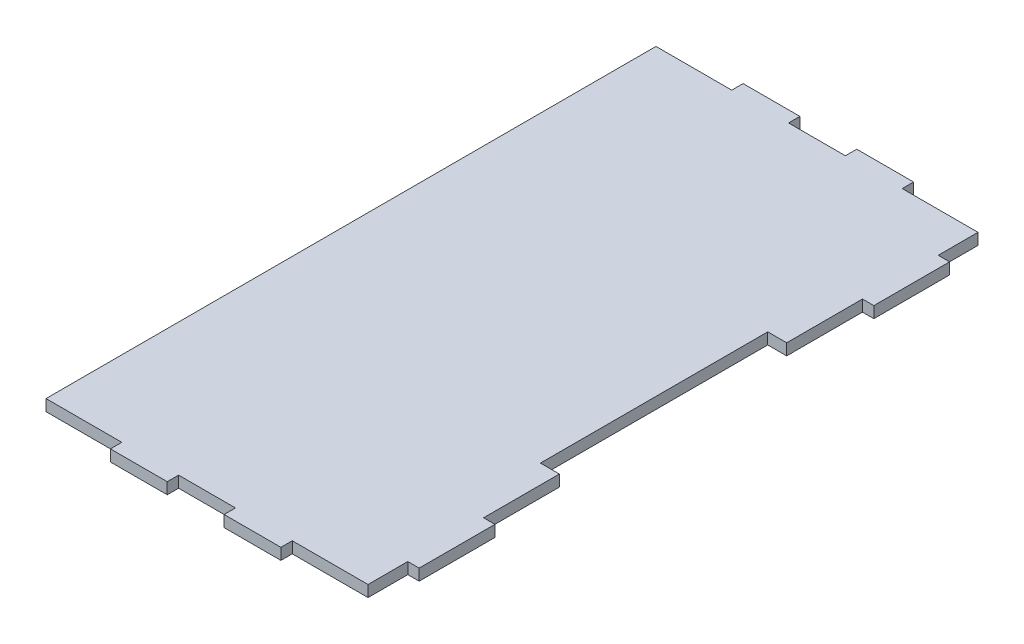
SolidWorks part; units mm, degrees
ref_plane "Alzado" through (0, 0, 0) normal (0, 0, 1) x (1, 0, 0)
ref_plane "Planta" through (0, 0, 0) normal (0, 1, 0) x (1, 0, 0)
ref_plane "Vista lateral" through (0, 0, 0) normal (1, 0, 0) x (0, 0, -1)
sketch "Croquis1" plane through (0, 0, 0) normal (0, 1, 0) x (1, 0, 0)
  line L0 (25.5, -0.5) -> (40.5, -0.5)
  line L1 (93.5, 13) -> (93.5, 33)
  line L2 (90.5, 163.5) -> (70.5, 163.5)
  line L3 (90.5, 113) -> (85.5, 113)
  line L4 (5.5, 163.5) -> (5.5, 2.5)
  line L5 (5.5, 73) -> (5.5, 93)
  line L6 (55.5, 166.5) -> (70.5, 166.5)
  line L7 (55.5, 163.5) -> (55.5, 166.5)
  line L8 (70.5, 166.5) -> (70.5, 163.5)
  line L9 (5.5, 113) -> (5.5, 133)
  line L10 (25.5, 166.5) -> (25.5, 163.5)
  line L11 (40.5, 166.5) -> (25.5, 166.5)
  line L12 (40.5, 163.5) -> (40.5, 166.5)
  line L13 (25.5, 166.5) -> (40.5, 166.5)
  line L14 (25.5, 163.5) -> (5.5, 163.5)
  line L15 (5.5, 53) -> (5.5, 33)
  line L16 (55.5, 163.5) -> (40.5, 163.5)
  line L17 (40.5, 2.5) -> (55.5, 2.5)
  line L18 (5.5, 153) -> (5.5, 163.5)
  line L19 (5.5, 13) -> (5.5, 2.5)
  line L20 (70.5, 2.5) -> (90.5, 2.5)
  line L21 (55.5, 2.5) -> (40.5, 2.5)
  line L22 (40.5, 2.5) -> (40.5, -0.5)
  line L23 (40.5, -0.5) -> (25.5, -0.5)
  line L24 (25.5, -0.5) -> (25.5, 2.5)
  line L25 (25.5, 2.5) -> (5.5, 2.5)
  line L26 (70.5, 2.5) -> (90.5, 2.5)
  line L27 (70.5, -0.5) -> (70.5, 2.5)
  line L28 (55.5, 2.5) -> (55.5, -0.5)
  line L29 (90.5, 13) -> (90.5, 2.5)
  line L30 (90.5, 153) -> (90.5, 163.5)
  line L33 (90.5, 53) -> (90.5, 33)
  line L34 (90.5, 33) -> (93.5, 33)
  line L35 (93.5, 13) -> (90.5, 13)
  line L36 (93.5, 153) -> (90.5, 153)
  line L37 (90.5, 133) -> (93.5, 133)
  line L38 (90.5, 113) -> (90.5, 133)
  line L42 (93.5, 133) -> (93.5, 153)
  line L43 (55.5, -0.5) -> (70.5, -0.5)
  line L46 (85.5, 113) -> (85.5, 53)
  line L47 (85.5, 53) -> (90.5, 53)
  line L48 (5.5, 2.5) -> (25.5, 2.5)
  line L49 (5.5, 163.5) -> (5.5, 13)
  dimension "D4" = 85
  dimension "D2" = 10.5
  dimension "D3" = 10.5
  dimension "D5" = 5
  dimension "D6" = 20
  dimension "D8" = 10.5
  dimension "D9" = 10.5
  dimension "D10" = 15
  dimension "D11" = 20
  dimension "D12" = 20
  dimension "D13" = 3
extrude "Saliente-Extruir1" add sketch "Croquis1" along normal blind 3
